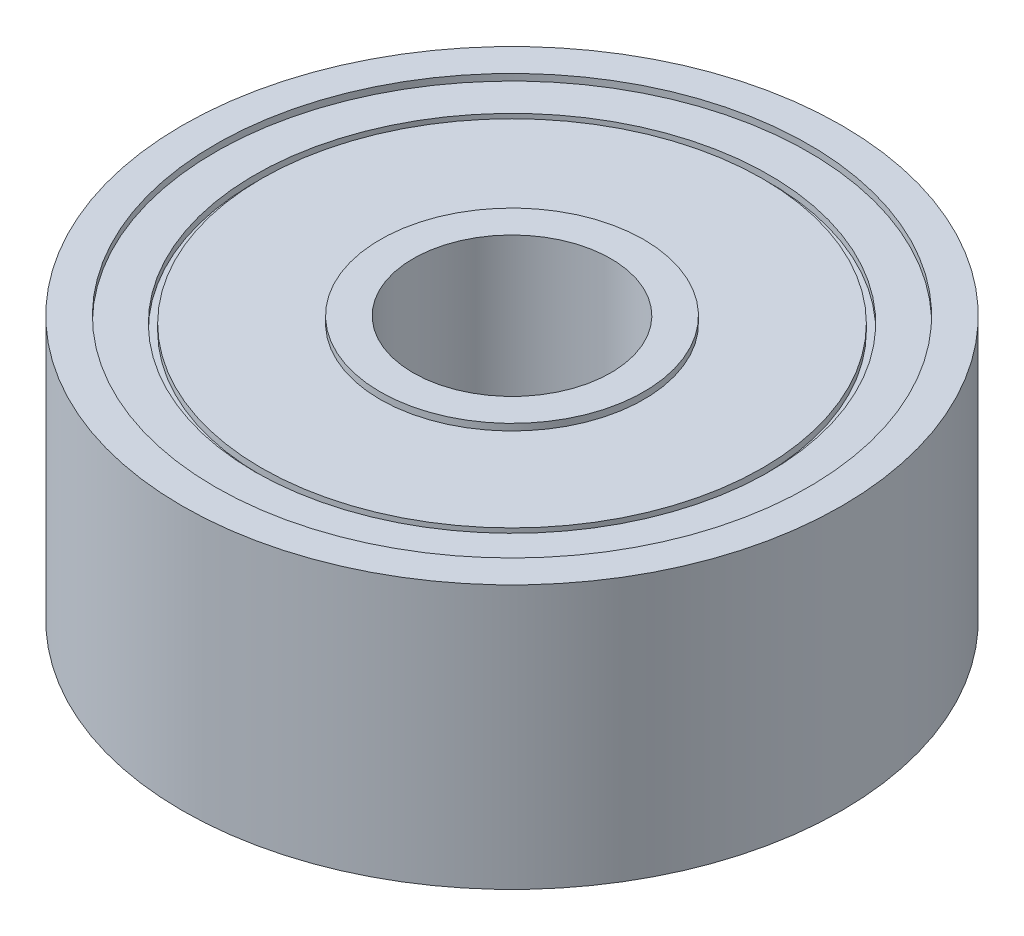
SolidWorks part; units mm, degrees
ref_plane "Спереди" through (0, 0, 0) normal (0, 0, 1) x (1, 0, 0)
ref_plane "Сверху" through (0, 0, 0) normal (0, 1, 0) x (1, 0, 0)
ref_plane "Справа" through (0, 0, 0) normal (1, 0, 0) x (0, 0, -1)
sketch "Эскиз1" plane through (0, 0, 0) normal (0, 1, 0) x (1, 0, 0)
  circle A0 centre (0, 0) radius 5
  circle A1 centre (0, 0) radius 1.5
  dimension "D1" = 10
  dimension "D2" = 3
extrude "Бобышка-Вытянуть1" add sketch "Эскиз1" along normal mid plane 4
sketch "Эскиз2" plane through (0, 2, 0) normal (0, 1, 0) x (1, 0, 0)
  circle A0 centre (0, 0) radius 2
  circle A1 centre (0, 0) radius 4.5
  circle A2 centre (0, 0) radius 5 construction
  dimension "D1" = 4
  dimension "D2" = 0.5
extrude "Вырез-Вытянуть1" cut sketch "Эскиз2" against normal blind 0.1
sketch "Эскиз4" plane through (0, 1.9, 0) normal (0, 1, 0) x (1, 0, 0)
  circle A0 centre (0, 0) radius 3.9
  circle A1 centre (0, 0) radius 4.5 construction
  circle A2 centre (0, 0) radius 3.8
  dimension "D1" = 0.6
  dimension "D2" = 0.1
extrude "Вырез-Вытянуть2" cut sketch "Эскиз4" against normal blind 0.1
mirror "Зеркальное отражение1" about plane through (0, 0, 0) normal (0, 1, 0) of "Вырез-Вытянуть2", "Вырез-Вытянуть1"
